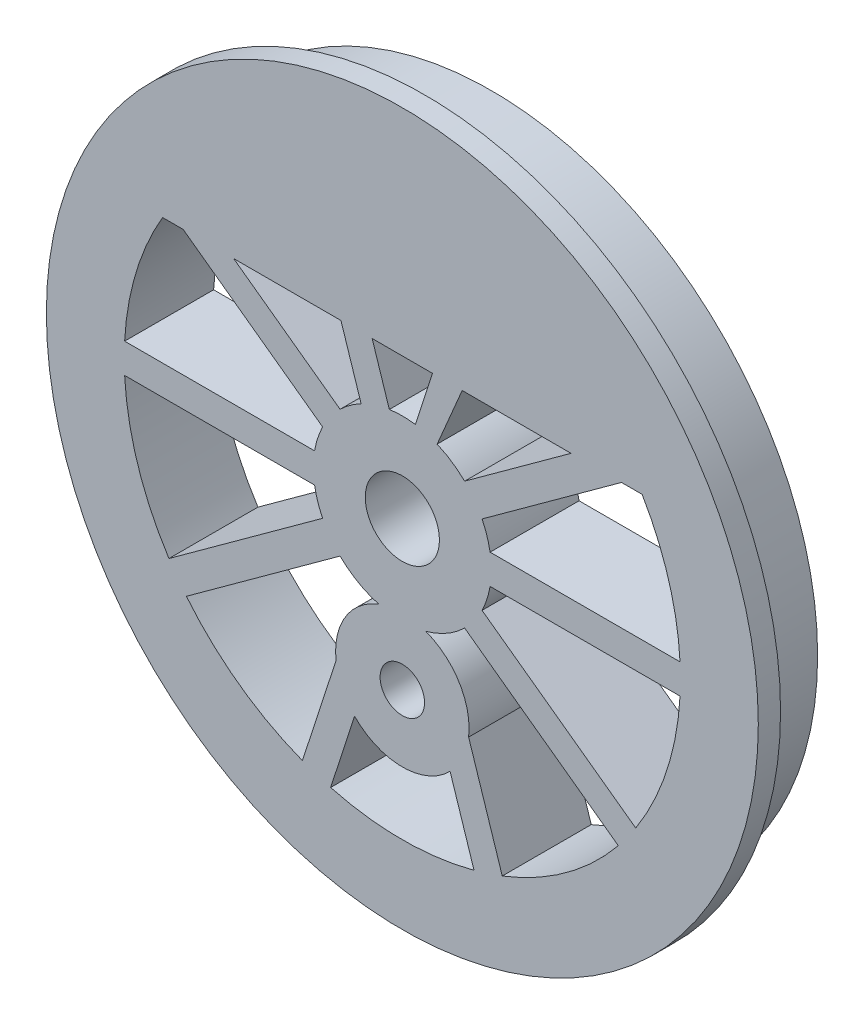
SolidWorks part; units mm, degrees
ref_plane "Plan de face" through (0, 0, 0) normal (0, 0, 1) x (1, 0, 0)
ref_plane "Plan de dessus" through (0, 0, 0) normal (0, 1, 0) x (1, 0, 0)
ref_plane "Plan de droite" through (0, 0, 0) normal (1, 0, 0) x (0, 0, -1)
sketch "Esquisse1" plane through (0, 0, 0) normal (0, 0, 1) x (1, 0, 0)
  line L0 (0, 0) -> (0, -10) construction
  line L1 (5.374, -2.6684) -> (18.3678, -12.1089)
  line L2 (3.2193, -13.1442) -> (5.8403, -21.2106)
  line L3 (0, 0) -> (0, 27.2327) construction
  line L4 (4.4698, -10.5205) -> (7.7424, -20.5926)
  line L5 (5.9161, 1) -> (21.9773, 1)
  line L6 (-21.9773, 1) -> (-21.9773, -1) construction
  line L8 (-21.9773, -1) -> (21.7985, -1) construction
  line L10 (0, 0) -> (0, -25.2075) construction
  line L11 (-5.374, -2.6684) -> (-18.3678, -12.1089)
  line L12 (-16.1652, 9.5) -> (16.1652, 9.5)
  line L13 (-18.75, 0) -> (18.75, 0) construction
  line L14 (-4.1984, -4.2864) -> (-17.1922, -13.7269)
  line L15 (5.374, 2.6684) -> (18.3678, 12.1089)
  line L16 (5.9161, -1) -> (21.9773, -1)
  line L17 (-5.9161, -1) -> (-21.9773, -1)
  line L18 (-5.8403, -21.2106) -> (-3.2193, -13.1442)
  line L19 (-7.7424, -20.5926) -> (-4.4698, -10.5205)
  line L20 (-21.9773, 1) -> (-5.9161, 1)
  line L21 (4.1984, 4.2864) -> (17.1922, 13.7269)
  line L22 (4.4698, 10.5205) -> (7.7424, 20.5926)
  line L23 (3.2193, 13.1442) -> (5.8403, 21.2106)
  line L24 (4.1984, -4.2864) -> (17.1922, -13.7269)
  line L25 (-5.8403, 21.2106) -> (-3.2193, 13.1442)
  line L26 (-7.7424, 20.5926) -> (-4.4698, 10.5205)
  line L27 (-4.1984, 4.2864) -> (-17.1922, 13.7269)
  line L28 (-5.374, 2.6684) -> (-18.3678, 12.1089)
  line L29 (-4.4698, 10.5205) -> (-2.7792, 5.3175)
  line L30 (-3.2193, 13.1442) -> (-0.8771, 5.9355)
  line L31 (4.4698, 10.5205) -> (2.3462, 5.5223)
  line L32 (3.2193, 13.1442) -> (0.8771, 5.9355)
  circle A0 centre (0, 0) radius 6
  circle A1 centre (0, 0) radius 2.5
  arc A3 (1.5827, -5.7875) -> (-1.5827, -5.7875) centre (0, -10) cw
  circle A4 centre (0, -10) radius 1.5
  circle A5 centre (0, 0) radius 22
  circle A6 centre (0, 0) radius 18.75
  circle A7 centre (0, 0) radius 19.5
  point P4 (0, -10)
  point P13 (0, 0)
  point P24 (0, 0)
  point P38 (0, 9.5)
  point P44 (0, 0)
  point P47 (0, 0)
  dimension "D1" = 12
  dimension "D2" = 5
  dimension "D4" = 4.5
  dimension "D5" = 3
  dimension "D6" = 44
  dimension "D9" = 37.5
  dimension "D22" = 39
  dimension "D23" = 9.5
  dimension "D3" = 10
  dimension "D8" = 2
  dimension "D10" = 8.4816
  dimension "D11" = 1
  dimension "D7" = 16.0612
  dimension "D12" = 16.0612
  dimension "D13" = 36
  dimension "D14" = 108
  dimension "D15" = 1
  dimension "D16" = 2
  dimension "D17" = 2
  dimension "D18" = 36
  dimension "D19" = 8.4816
  dimension "D20" = 1
  dimension "D21" = 2
extrude "Boss.-Extru.1" add sketch "Esquisse1" along normal blind 6 contours A0 A1 | A0 L27 L12 L28 | L26 A6 L27 L12 L29 | L25 A6 L26 L29 L12 L30 | L23 A6 L25 L30 L12 L32 | L22 A6 L23 L32 L12 L31 | L21 A6 L22 L31 L12 | L15 A6 L21 L12 | A0 L15 L12 L21 | A0 L31 L12 L32 | A0 L30 L12 L29 | L11 A6 L14 A0 | L20 A6 L17 A0 | L16 A6 L5 A0 | L1 A7 L16 A6 | L16 A7 L5 A6 | L5 A7 L15 A6 | L15 A7 L21 A6 | L21 A7 L22 A6 | L22 A7 L23 A6 | L23 A7 L25 A6 | L25 A7 L26 A6 | L26 A7 L27 A6 | L27 A7 L28 A6 | L28 A7 L20 A6 | L20 A7 L17 A6 | L17 A7 L11 A6 | L11 A7 L14 A6 | A7 L18 A5 L2 | A7 L11 A5 L14 | A7 L19 A5 L18 | L19 A6 L18 A3 | L2 A6 L4 A3 | A7 L2 A5 L4 | A7 L4 A5 L24 | L24 A7 L1 A6 | L4 A7 L24 A6 | L24 A6 L1 A0 | L27 A6 L28 L12 | L28 A6 L12 | L12 A6 L15 | A7 L15 A5 L21 | A7 L5 A5 L15 | A7 L16 A5 L5 | A7 L1 A5 L16 | A7 L24 A5 L1 | A7 L21 A5 L22 | A7 L22 A5 L23 | A7 L25 A5 L26 | A7 L26 A5 L27 | A7 L23 A5 L25 | A7 L27 A5 L28 | A7 L28 A5 L20 | A7 L17 A5 L11 | A7 L20 A5 L17 | A7 L14 A5 L19 | L14 A7 L19 A6 | L19 A7 L18 A6 | L18 A7 L2 A6 | L2 A7 L4 A6 | A3 A0 A4
sketch "Esquisse3" plane through (0, 0, 6) normal (0, 0, 1) x (1, 0, 0)
  circle A0 centre (0, 0) radius 24
  circle A1 centre (0, 0) radius 22
  dimension "D1" = 48
  dimension "D2" = 44
extrude "Boss.-Extru.2" add sketch "Esquisse3" against normal blind 1.5
